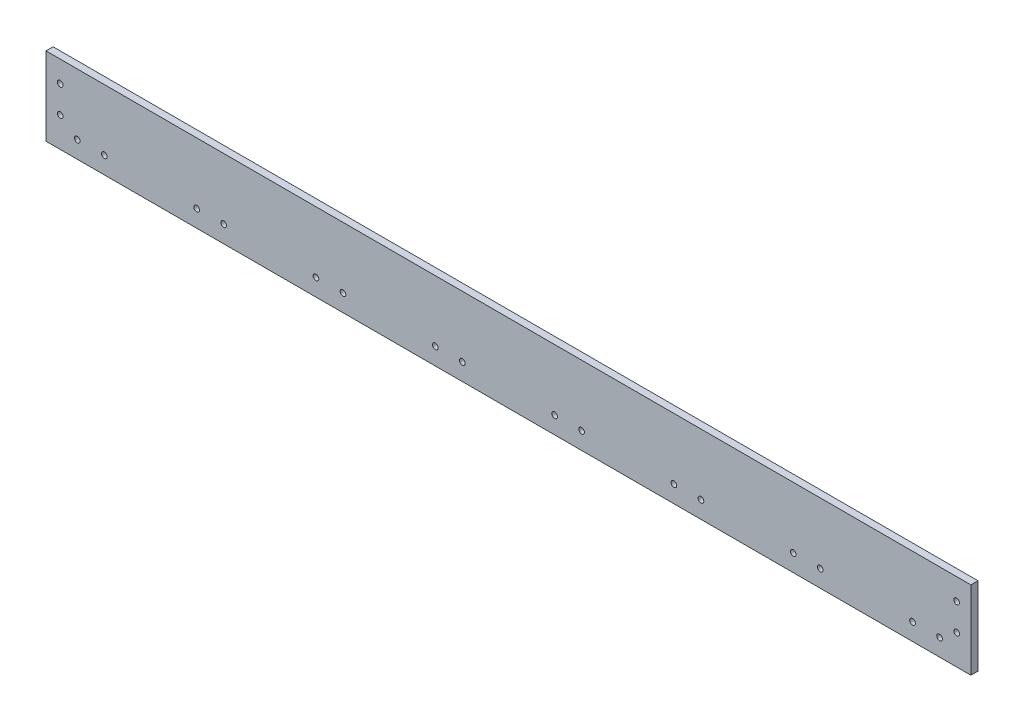
SolidWorks part; units mm, degrees
ref_plane "Front Plane" through (0, 0, 0) normal (0, 0, 1) x (1, 0, 0)
ref_plane "Top Plane" through (0, 0, 0) normal (0, 1, 0) x (1, 0, 0)
ref_plane "Right Plane" through (0, 0, 0) normal (1, 0, 0) x (0, 0, -1)
sketch "Sketch1" plane through (0, 0, 0) normal (0, 0, 1) x (1, 0, 0)
  line L1 (0, 0) -> (825.5, 0)
  line L2 (0, 0) -> (0, 69.85)
  line L3 (0, 69.85) -> (825.5, 69.85)
  line L4 (825.5, 0) -> (825.5, 69.85)
  dimension "D1" = 69.85
  dimension "D2" = 825.5
extrude "Boss-Extrude1" add sketch "Sketch1" along normal blind 6.35
sketch "Sketch2" plane through (0, 0, 6.35) normal (0, 0, 1) x (1, 0, 0)
  line L0 (27.94, 0) -> (27.94, 12.7) construction
  line L2 (0, 15.24) -> (25.4, 15.24) construction
  line L3 (0, 69.85) -> (0, 0) construction
  line L4 (0, 0) -> (825.5, 0) construction
  line L5 (30.48, 15.24) -> (49.53, 15.24) construction
  circle A0 centre (27.94, 15.24) radius 2.54
  circle A1 centre (52.07, 15.24) radius 2.54
  point P13 (1219.2, 76.2)
  dimension "D2" = 5.08
  dimension "D1" = 5.08
  dimension "D3" = 19.05
  dimension "D5" = 12.7
  dimension "D4" = 25.4
extrude "Cut-Extrude1" cut sketch "Sketch2" against normal up to surface (6.35 mm away) contours A1 | A0 up to face at (412.75, 34.925, 0)
sketch "Sketch3" plane through (0, 0, 6.35) normal (0, 0, 1) x (1, 0, 0)
  line L0 (0, 69.85) -> (0, 0) construction
  line L1 (825.5, 69.85) -> (0, 69.85) construction
  line L2 (12.7, 38.735) -> (0, 38.735) construction
  line L3 (12.7, 48.26) -> (12.7, 29.21) construction
  line L4 (0, 38.735) -> (0, 34.925) construction
  line L5 (412.75, 69.85) -> (412.75, 0) construction
  line L6 (0, 0) -> (825.5, 0) construction
  circle A0 centre (12.7, 26.67) radius 2.54
  circle A1 centre (12.7, 50.8) radius 2.54
  circle A2 centre (812.8, 26.67) radius 2.54
  circle A3 centre (812.8, 50.8) radius 2.54
  point P13 (0, 34.925)
  point P15 (412.75, 69.85)
  point P17 (12.7, 38.735)
  point P27 (12.7, 38.735)
  dimension "D2" = 5.08
  dimension "D1" = 5.08
  dimension "D3" = 19.05
  dimension "D4" = 12.7
  dimension "D5" = 3.81
extrude "Cut-Extrude2" cut sketch "Sketch3" against normal up to surface (6.35 mm away) up to face at (25.4, 15.24, 0)
pattern_linear "LPattern2" count 8 spacing 106.4986 along (1, 0, 0) of "Cut-Extrude1"
equation "\"vertical-component-width\"= \"railing-width\" - \"railing-padding\""
equation "\"vertical-component-height\"= 2.75in"
equation "\"material-thickness\"= .25in"
equation "\"D1@Sketch1\"=\"vertical-component-height\""
equation "\"D2@Sketch1\"=\"vertical-component-width\""
equation "\"D1@Boss-Extrude1\"=\"material-thickness\""
equation "\"mounting-hole-diameter\"= .2"
equation "\"mounting-hole-pair-left-to-mount-edge-left\"= 1in"
equation "\"mounting-hole-bottom-to-mount-edge-bottom\"= .5in"
equation "\"mounting-hole-pair-distance-between-holes\"= .75in"
equation "\"distance-between-mounting-hole-pairs\"= ( \"vertical-component-width\" - 2 * \"mounting-hole-pair-left-to-mount-edge-left\" - \"num-mounting-hole-pairs\" * ( 2 * \"mounting-hole-diameter\" + \"mounting-hole-pair-distance-between-holes\" ) ) / ( \"num-mounting-hole-pairs\" - 1 )"
equation "\"num-mounting-hole-pairs\"= 8"
equation "\"D3@Sketch2\"=\"mounting-hole-pair-distance-between-holes\""
equation "\"D5@Sketch2\"=\"mounting-hole-bottom-to-mount-edge-bottom\""
equation "\"D4@Sketch2\"=\"mounting-hole-pair-left-to-mount-edge-left\""
equation "\"D3@LPattern2\"=\"mounting-hole-pair-left-to-next-mounting-hole-pair-left\""
equation "\"D2@Sketch2\"=\"mounting-hole-diameter\""
equation "\"D1@Sketch2\"=\"mounting-hole-diameter\""
equation "\"mounting-hole-pair-left-to-next-mounting-hole-pair-left\"= \"distance-between-mounting-hole-pairs\" + 2 * \"mounting-hole-diameter\" + \"mounting-hole-pair-distance-between-holes\""
equation "\"edge-mounting-hole-pair-inset\"=0.5"
equation "\"D4@Sketch3\"=\"edge-mounting-hole-pair-inset\""
equation "\"edge-mounting-hole-pair-offset-from-mount-vertical-center\"= 0.15"
equation "\"D5@Sketch3\"=\"edge-mounting-hole-pair-offset-from-mount-vertical-center\""
equation "\"D3@Sketch3\"=\"mounting-hole-pair-distance-between-holes\""
equation "\"railing-width\"= 33in"
equation "\"railing-padding\"= .5in"
equation "\"D1@LPattern2\"=\"num-mounting-hole-pairs\""
